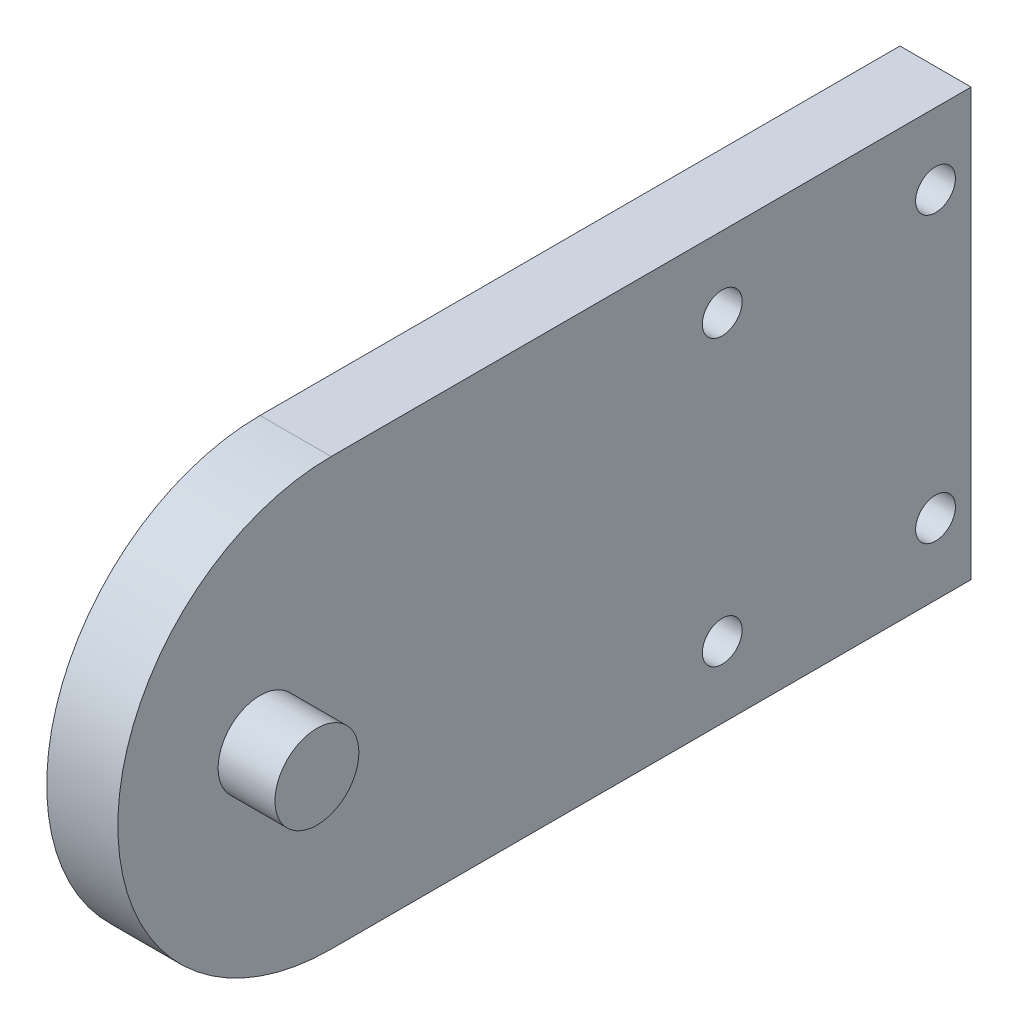
SolidWorks part; units mm, degrees
ref_plane "Front Plane" through (0, 0, 0) normal (0, 0, 1) x (1, 0, 0)
ref_plane "Top Plane" through (0, 0, 0) normal (0, 1, 0) x (1, 0, 0)
ref_plane "Right Plane" through (0, 0, 0) normal (1, 0, 0) x (0, 0, -1)
sketch "Sketch1" plane through (0, 0, 0) normal (0, 1, 0) x (1, 0, 0)
  line L1 (-2.5, 30) -> (2.5, 30)
  line L2 (-2.5, 30) -> (-2.5, -30)
  line L3 (-2.5, -30) -> (2.5, -30)
  line L4 (2.5, 30) -> (2.5, -30)
  point P4 (0, 30)
  point P6 (-2.5, 0)
  dimension "D1" = 5
  dimension "D2" = 60
extrude "Boss-Extrude1" add sketch "Sketch1" along normal blind 30
sketch "Sketch2" plane through (2.5, 0, 0) normal (1, 0, 0) x (0, 0, -1)
  line L0 (-30, 30) -> (-30, 0) construction
  line L2 (-20, 15) -> (-20, 22) construction
  circle A0 centre (-20, 15) radius 2.95
  point P4 (-30, 15)
  dimension "D1" = 5.9
  dimension "D2" = 10
sketch "Sketch3" plane through (-2.5, 0, 0) normal (-1, 0, 0) x (0, 0, 1)
  line L0 (-30, 15) -> (30, 15) construction
  line L1 (-30, 30) -> (-30, 0) construction
  line L2 (30, 30) -> (30, 0) construction
  line L3 (-30, 30) -> (30, 30) construction
  circle A0 centre (-27.5, 25) radius 1.4
  circle A1 centre (-12.5, 25) radius 1.4
  circle A2 centre (-12.5, 5) radius 1.4
  circle A3 centre (-27.5, 5) radius 1.4
  dimension "D1" = 2.8
  dimension "D2" = 5
  dimension "D3" = 15
  dimension "D4" = 2.5
extrude "Cut-Extrude1" cut sketch "Sketch3" against normal blind 6
extrude "Boss-Extrude2" add sketch "Sketch2" along normal blind 4
sketch "Sketch4" plane through (-2.5, 0, 0) normal (-1, 0, 0) x (0, 0, 1)
  line L0 (30, 15) -> (15, 15) construction
  line L1 (30, 30) -> (30, 0) construction
  line L2 (15, 15) -> (15, 30) construction
  line L3 (-30, 30) -> (30, 30) construction
  line L4 (-30, 0) -> (30, 0) construction
  line L5 (15, 30) -> (30, 30)
  line L6 (30, 30) -> (30, 15)
  line L7 (15, 0) -> (30, 0)
  line L8 (30, 0) -> (30, 15)
  arc A0 (15, 30) -> (30, 15) centre (15, 15) cw
  arc A1 (15, 0) -> (30, 15) centre (15, 15) ccw
extrude "Cut-Extrude2" cut sketch "Sketch4" against normal blind 10 contours L6 L5 A0 | A1 L7 L8
